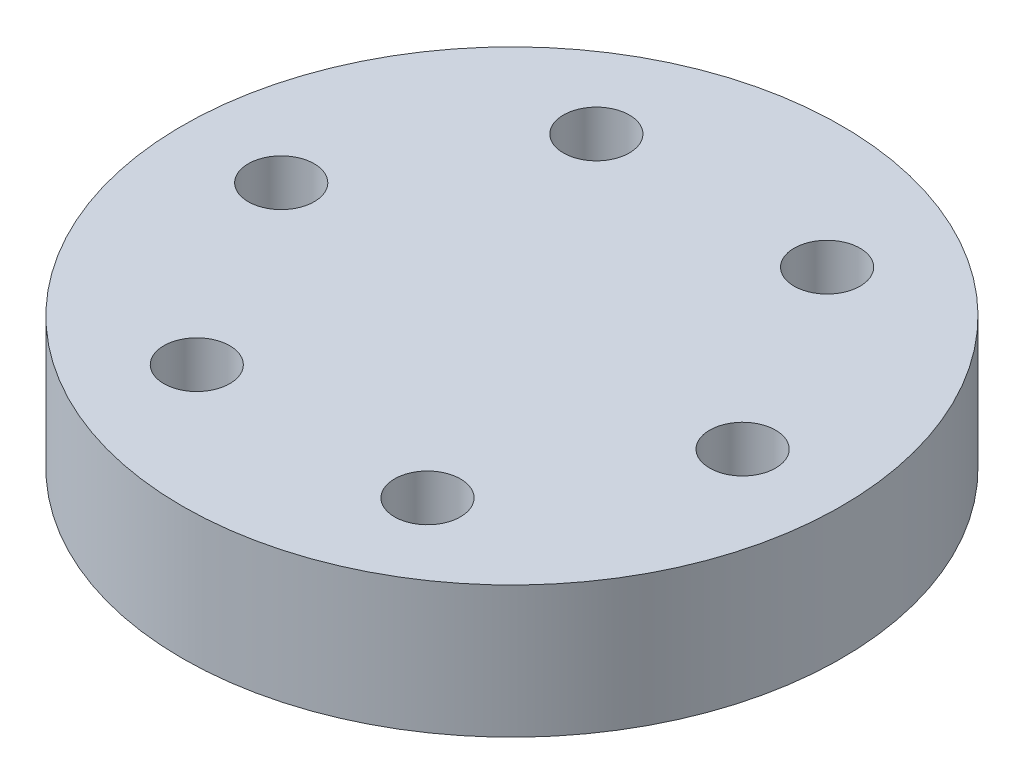
SolidWorks part; units mm, degrees
ref_plane "Front Plane" through (0, 0, 0) normal (0, 0, 1) x (1, 0, 0)
ref_plane "Top Plane" through (0, 0, 0) normal (0, 1, 0) x (1, 0, 0)
ref_plane "Right Plane" through (0, 0, 0) normal (1, 0, 0) x (0, 0, -1)
sketch "Sketch1" plane through (0, 0, 0) normal (0, 1, 0) x (1, 0, 0)
  circle A0 centre (0, 0) radius 50
  dimension "D1" = 100
extrude "Boss-Extrude1" add sketch "Sketch1" along normal blind 20
sketch "Sketch2" plane through (0, 20, 0) normal (0, 1, 0) x (1, 0, 0)
  circle A0 centre (0, 0) radius 35
  circle A1 centre (-35, 0) radius 5
  circle A2 centre (-17.5, 30.3109) radius 5
  circle A3 centre (17.5, 30.3109) radius 5
  circle A4 centre (35, 0) radius 5
  circle A5 centre (17.5, -30.3109) radius 5
  circle A6 centre (-17.5, -30.3109) radius 5
  point P5 (-21.7628, -35.2576)
  point P6 (0, 0)
  point P7 (0, 0)
  point P18 (0, 0)
  dimension "D1" = 70
  dimension "D2" = 10
  dimension "D3" = 6
extrude "Cut-Extrude2" cut sketch "Sketch2" against normal blind 10 contours A0 A1 | A0 A1 | A0 A6 | A0 A6 | A0 A5 | A0 A5 | A0 A4 | A0 A4 | A0 A3 | A0 A3 | A0 A2 | A0 A2
